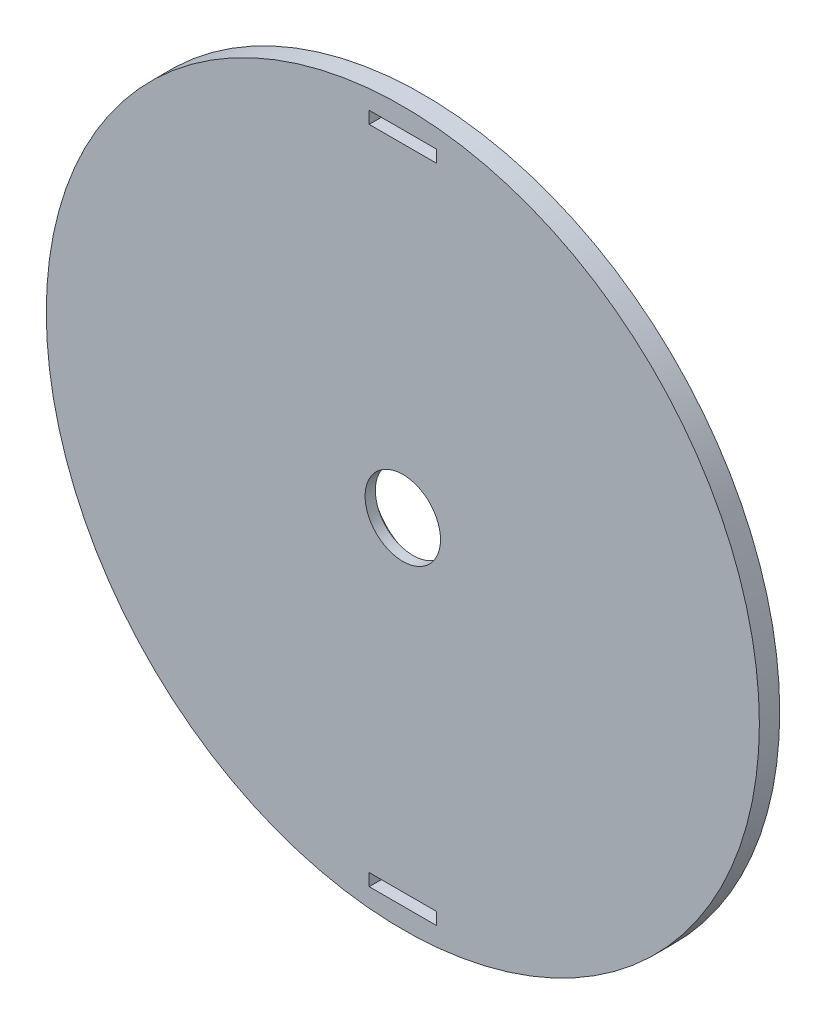
SolidWorks part; units mm, degrees
ref_plane "前视基准面" through (0, 0, 0) normal (0, 0, 1) x (1, 0, 0)
ref_plane "上视基准面" through (0, 0, 0) normal (0, 1, 0) x (1, 0, 0)
ref_plane "右视基准面" through (0, 0, 0) normal (1, 0, 0) x (0, 0, -1)
other "Configuration Table"
sketch "草图1" plane through (0, 0, 0) normal (0, 0, 1) x (1, 0, 0)
  circle A0 centre (0, 0) radius 87.5
  dimension "D1" = 175
extrude "凸台-拉伸1" add sketch "草图1" along normal blind 5
sketch "草图7" plane through (0, 0, 0) normal (0, 0, -1) x (-1, 0, 0)
  line L1 (-8.25, 82.5) -> (8.25, 82.5)
  line L2 (-8.25, 82.5) -> (-8.25, 79.5)
  line L3 (-8.25, 79.5) -> (8.25, 79.5)
  line L4 (8.25, 82.5) -> (8.25, 79.5)
  line L5 (0, 79.5) -> (0, 82.5) construction
  line L6 (-8.25, 81) -> (8.25, 81) construction
  point P0 (0, 81)
  dimension "D1" = 81
  dimension "D2" = 16.5
  dimension "D3" = 3
extrude "切除-拉伸3" cut sketch "草图7" against normal blind 10
pattern_circular "阵列(圆周)1" count 2 over 360 about axis through (0, 0, 0) along (0, 0, 1) of "切除-拉伸3"
sketch "草图8" plane through (0, 0, 0) normal (0, 0, -1) x (-1, 0, 0)
  line L5 (-8.25, 79.5) -> (8.25, 79.5) construction
  line L6 (-8.05, 79.5) -> (8.05, 79.5)
  line L7 (-8.05, 79.5) -> (-8.05, 49.5)
  line L8 (-8.05, 49.5) -> (8.05, 49.5)
  line L9 (8.05, 79.5) -> (8.05, 49.5)
  line L10 (-8.25, 82.5) -> (-8.25, 79.5) construction
  line L11 (8.25, 79.5) -> (8.25, 82.5) construction
  dimension "D1" = 0.2
  dimension "D2" = 0.2
  dimension "D3" = 30
extrude "切除-拉伸4" cut sketch "草图8" against normal blind 2
pattern_circular "阵列(圆周)2" count 2 over 360 about axis through (0, 0, 0) along (0, 0, 1) of "切除-拉伸4"
sketch "草图9" plane through (0, 0, 5) normal (0, 0, 1) x (1, 0, 0)
  circle A0 centre (0, 0) radius 9.25
  dimension "D1" = 18.5
extrude "切除-拉伸5" cut sketch "草图9" against normal blind 2.5
sketch "草图10" plane through (0, 0, 0) normal (0, 0, -1) x (-1, 0, 0)
  circle A0 centre (0, 0) radius 12.6
  dimension "D1" = 25.2
extrude "切除-拉伸6" cut sketch "草图10" against normal blind 2.5
